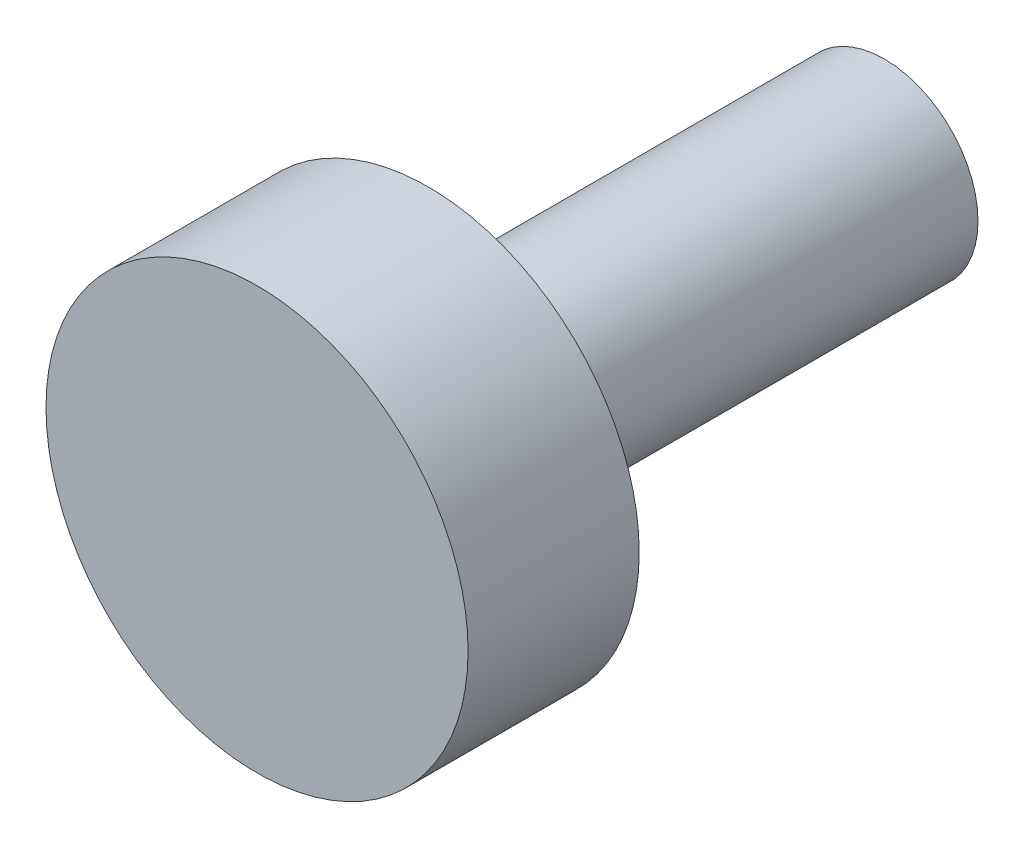
SolidWorks part; units mm, degrees
ref_plane "前视基准面" through (0, 0, 0) normal (0, 0, 1) x (1, 0, 0)
ref_plane "上视基准面" through (0, 0, 0) normal (0, 1, 0) x (1, 0, 0)
ref_plane "右视基准面" through (0, 0, 0) normal (1, 0, 0) x (0, 0, -1)
other "Configuration Table"
sketch "Profile_1" plane through (0, 0, 0) normal (0, 0, 1) x (1, 0, 0)
  circle A0 centre (0, 0) radius 1.64
extrude "Thread_envelope" add sketch "Profile_1" along normal blind 8 from offset 1
sketch "Profile_2" plane through (0, 0, 0) normal (0, 0, 1) x (1, 0, 0)
  circle A0 centre (0, 0) radius 3.7
extrude "Screw_head" add sketch "Profile_2" along normal blind 3 from offset 9
